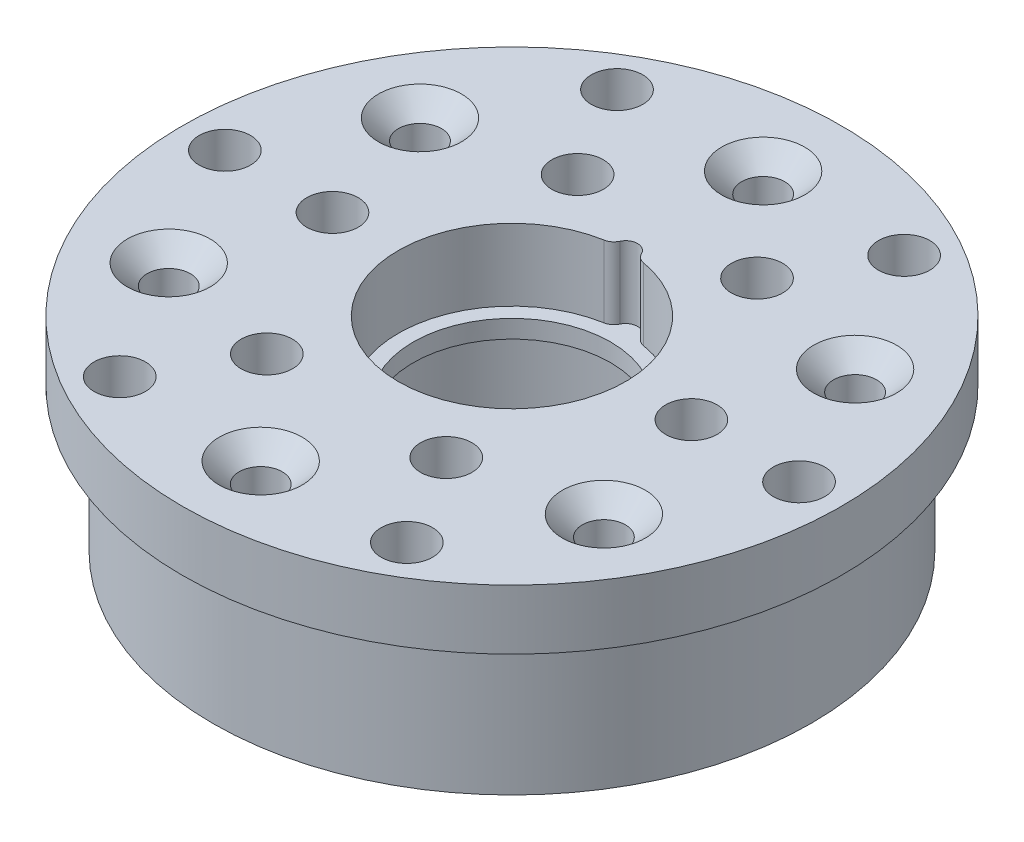
SolidWorks part; units mm, degrees
ref_plane "Front Plane" through (0, 0, 0) normal (0, 0, 1) x (1, 0, 0)
ref_plane "Top Plane" through (0, 0, 0) normal (0, 1, 0) x (1, 0, 0)
ref_plane "Right Plane" through (0, 0, 0) normal (1, 0, 0) x (0, 0, -1)
sketch "Sketch1" plane through (0, 0, 0) normal (0, 1, 0) x (1, 0, 0)
  circle A0 centre (0, 0) radius 21 construction
  circle A1 centre (0, 21) radius 2.5
  circle A2 centre (18.1865, 10.5) radius 2.5
  circle A3 centre (18.1865, -10.5) radius 2.5
  circle A4 centre (0, -21) radius 2.5
  circle A5 centre (-18.1865, -10.5) radius 2.5
  circle A6 centre (-18.1865, 10.5) radius 2.5
  circle A7 centre (0, 0) radius 25
  circle A8 centre (0, 0) radius 8.25
  point P18 (0, 0)
  dimension "D1" = 42
  dimension "D2" = 5
  dimension "D4" = 50
  dimension "D5" = 16.5
  dimension "D3" = 6
extrude "Boss-Extrude1" add sketch "Sketch1" along normal blind 10
sketch "Sketch2" plane through (0, 10, 0) normal (0, 1, 0) x (1, 0, 0)
  circle A0 centre (0, 0) radius 9.5
  circle A1 centre (0, 0) radius 15.5
  dimension "D1" = 19
  dimension "D2" = 6
extrude "Boss-Extrude2" add sketch "Sketch2" along normal blind 8.5
sketch "Sketch4" plane through (0, 10, 0) normal (0, 1, 0) x (1, 0, 0)
  circle A0 centre (0, 0) radius 9.5 construction
  circle A1 centre (0, 0) radius 8.25 construction
  circle A2 centre (0, 0) radius 9.5
  circle A3 centre (0, 0) radius 8.25
extrude "Boss-Extrude3" add sketch "Sketch4" along normal blind 2.5
sketch "Sketch3" plane through (0, 0, 0) normal (0, -1, 0) x (1, 0, 0)
  circle A0 centre (0, 0) radius 12.5
  dimension "D1" = 25
extrude "Cut-Extrude1" cut sketch "Sketch3" against normal blind 11
chamfer "Chamfer1" distance 3 angle 45 1 edges at (0, 11, -12.5)
sketch "Sketch5" plane through (0, 10, 0) normal (0, 1, 0) x (1, 0, 0)
  circle A0 centre (0, 21) radius 2.5
  circle A1 centre (18.1865, 10.5) radius 2.5
  circle A2 centre (18.1865, -10.5) radius 2.5
  circle A3 centre (0, -21) radius 2.5
  circle A4 centre (-18.1865, -10.5) radius 2.5
  circle A5 centre (-18.1865, 10.5) radius 2.5
  circle A6 centre (0, 0) radius 25 construction
  circle A7 centre (0, 0) radius 25
  circle A8 centre (0, 0) radius 15.5 construction
  circle A9 centre (0, 0) radius 15.5
  circle A10 centre (0, 21) radius 2.5 construction
  point P15 (0, 0)
  dimension "D2" = 6
extrude "Boss-Extrude4" add sketch "Sketch5" along normal blind 8.5
sketch "Sketch6" plane through (0, 18.5, 0) normal (0, 1, 0) x (1, 0, 0)
  circle A0 centre (0, 0) radius 25 construction
  circle A1 centre (0, 0) radius 25
  circle A2 centre (0, 0) radius 27.55
  dimension "D1" = 55.1
extrude "Boss-Extrude5" add sketch "Sketch6" against normal blind 5
sketch "Sketch8" plane through (0, 18.5, 0) normal (0, 1, 0) x (1, 0, 0)
  circle A0 centre (0, 9.5) radius 1
  circle A1 centre (0, 0) radius 9.5 construction
  circle A2 centre (0, 0) radius 9.5 construction
  dimension "D1" = 2
extrude "Cut-Extrude2" cut sketch "Sketch8" against normal up to surface (6 mm away) up to face at (0, 12.5, 9.5)
fillet "Fillet1" radius 1 2 edges at (0.9986, 15.5, -9.4474) (-0.9986, 15.5, -9.4474)
sketch "Sketch11" plane through (0, 18.5, 0) normal (0, 1, 0) x (1, 0, 0)
  line L0 (0, 0) -> (17.55, 30.3975) construction
  circle A0 centre (0, 0) radius 15 construction
  circle A1 centre (7.5, 12.9904) radius 2.15
  circle A2 centre (15, 0) radius 2.15
  circle A3 centre (7.5, -12.9904) radius 2.15
  circle A4 centre (-7.5, -12.9904) radius 2.15
  circle A5 centre (-15, 0) radius 2.15
  circle A6 centre (-7.5, 12.9904) radius 2.15
  circle A7 centre (0, 0) radius 24 construction
  circle A8 centre (-24, 0) radius 2.15
  circle A9 centre (-12, 20.7846) radius 2.15
  circle A10 centre (12, 20.7846) radius 2.15
  circle A11 centre (24, 0) radius 2.15
  circle A12 centre (12, -20.7846) radius 2.15
  circle A13 centre (-12, -20.7846) radius 2.15
  point P18 (0, 0)
  point P32 (0, 0)
  dimension "D2" = 30
  dimension "D3" = 4.3
  dimension "D5" = 48
  dimension "D1" = 60
  dimension "D4" = 6
extrude "Cut-Extrude3" cut sketch "Sketch11" against normal blind 4.8
sketch "Sketch12" plane through (0, 0, 0) normal (0, -1, 0) x (1, 0, 0)
  circle A0 centre (0, 0) radius 25 construction
  circle A1 centre (18.1865, 10.5) radius 2.5 construction
  circle A2 centre (18.1865, -10.5) radius 2.5 construction
  circle A3 centre (0, -21) radius 2.5 construction
  circle A4 centre (-18.1865, -10.5) radius 2.5 construction
  circle A5 centre (-18.1865, 10.5) radius 2.5 construction
  circle A6 centre (0, 21) radius 2.5 construction
  circle A7 centre (0, 0) radius 12.5 construction
  circle A8 centre (0, 0) radius 25
  circle A9 centre (18.1865, 10.5) radius 2.5
  circle A10 centre (18.1865, -10.5) radius 2.5
  circle A11 centre (0, -21) radius 2.5
  circle A12 centre (-18.1865, -10.5) radius 2.5
  circle A13 centre (-18.1865, 10.5) radius 2.5
  circle A14 centre (0, 21) radius 2.5
  circle A15 centre (0, 0) radius 12.5
extrude "Cut-Extrude4" cut sketch "Sketch12" against normal blind 1.5
sketch "Sketch14" plane through (0, 18.5, 0) normal (0, 1, 0) x (1, 0, 0)
  circle A0 centre (0, 21) radius 2.5 construction
  circle A1 centre (0, 21) radius 2.5
  circle A2 centre (0, 21) radius 1.5
  circle A3 centre (18.1865, 10.5) radius 1.5
  circle A4 centre (18.1865, 10.5) radius 2.5
  circle A5 centre (18.1865, -10.5) radius 1.5
  circle A6 centre (18.1865, -10.5) radius 2.5
  circle A7 centre (0, -21) radius 1.5
  circle A8 centre (0, -21) radius 2.5
  circle A9 centre (-18.1865, -10.5) radius 1.5
  circle A10 centre (-18.1865, -10.5) radius 2.5
  circle A11 centre (-18.1865, 10.5) radius 1.5
  circle A12 centre (-18.1865, 10.5) radius 2.5
  point P22 (0, 0)
  dimension "D1" = 3
extrude "Boss-Extrude8" add sketch "Sketch14" against normal blind 4.5
hole_wizard "CSK for M3 socket countersunk head screw1" positions "Sketch15" profile "Sketch16" countersink size "M3" standard "DIN" end condition through all
sketch "Sketch15" plane through (0, 18.5, 0) normal (0, 1, 0) x (1, 0, 0)
  point P0 (0, 21)
  point P3 (18.1865, 10.5)
  point P6 (18.1865, -10.5)
  point P9 (0, -21)
  point P12 (-18.1865, -10.5)
  point P15 (-18.1865, 10.5)
sketch "Sketch16" plane through (0, 18.5, -21) normal (1, 0, 0) x (0, 0, 1)
  line L0 (0, 0) -> (0, 17)
  line L1 (0, 17) -> (1.8, 17)
  line L2 (1.8, 17) -> (1.8, 1.67)
  line L3 (1.8, 1.67) -> (3.47, 0)
  line L5 (3.47, 0) -> (0, 0)
  line L6 (-1.8, 1.67) -> (-3.47, 0) construction
  line L11 (0, -6.35) -> (0, 107.95) construction
  dimension "Thru Hole Dia." = 3.6
  dimension "Thru Hole Depth" = 17
  dimension "Near C'Sink Dia." = 6.94
  dimension "Near C'Sink Angle" = 90
